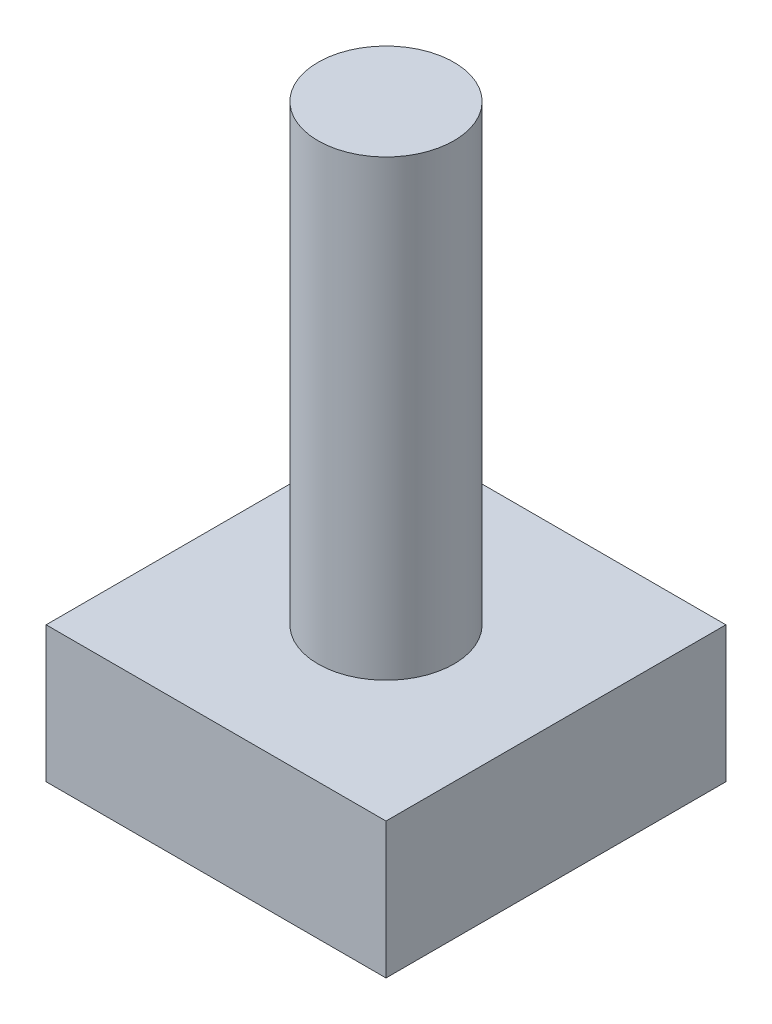
SolidWorks part; units mm, degrees
ref_plane "Front Plane" through (0, 0, 0) normal (0, 0, 1) x (1, 0, 0)
ref_plane "Top Plane" through (0, 0, 0) normal (0, 1, 0) x (1, 0, 0)
ref_plane "Right Plane" through (0, 0, 0) normal (1, 0, 0) x (0, 0, -1)
sketch "Sketch1" plane through (0, 0, 0) normal (0, 1, 0) x (1, 0, 0)
  line L5 (0, 0) -> (15, 0)
  line L6 (0, 0) -> (0, 15)
  line L7 (0, 15) -> (15, 15)
  line L8 (15, 0) -> (15, 15)
  dimension "D1" = 15
  dimension "D2" = 15
extrude "Boss-Extrude1" add sketch "Sketch1" along normal blind 6
sketch "Sketch2" plane through (0, 6, 0) normal (0, 1, 0) x (1, 0, 0)
  line L0 (15, 15) -> (0, 15) construction
  line L1 (15, 0) -> (15, 15) construction
  circle A0 centre (7.5, 7.5) radius 3
  point P4 (7.5, 15)
  point P9 (15, 7.5)
  dimension "D1" = 6
extrude "Boss-Extrude2" add sketch "Sketch2" along normal blind 20
